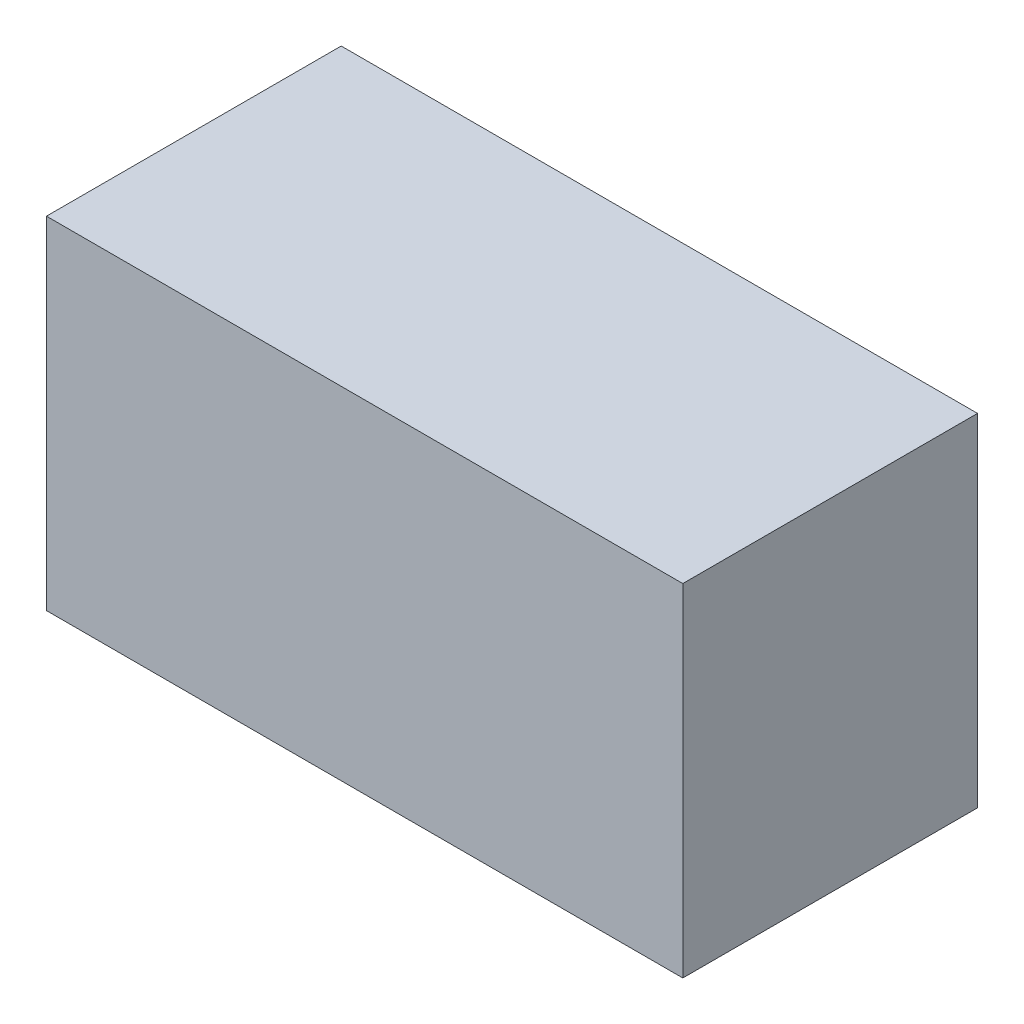
SolidWorks part; units mm, degrees
ref_plane "Front Plane" through (0, 0, 0) normal (0, 0, 1) x (1, 0, 0)
ref_plane "Top Plane" through (0, 0, 0) normal (0, 1, 0) x (1, 0, 0)
ref_plane "Right Plane" through (0, 0, 0) normal (1, 0, 0) x (0, 0, -1)
sketch "Sketch1" plane through (0, 0, 0) normal (0, 1, 0) x (1, 0, 0)
  line L1 (-47.5, -22) -> (47.5, -22)
  line L2 (-47.5, -22) -> (-47.5, 22)
  line L3 (-47.5, 22) -> (47.5, 22)
  line L4 (47.5, -22) -> (47.5, 22)
  line L5 (-47.5, -22) -> (47.5, 22) construction
  line L6 (-47.5, 22) -> (47.5, -22) construction
  point P0 (0, 0)
  dimension "D1" = 95
  dimension "D2" = 44
extrude "Boss-Extrude1" add sketch "Sketch1" along normal blind 51
